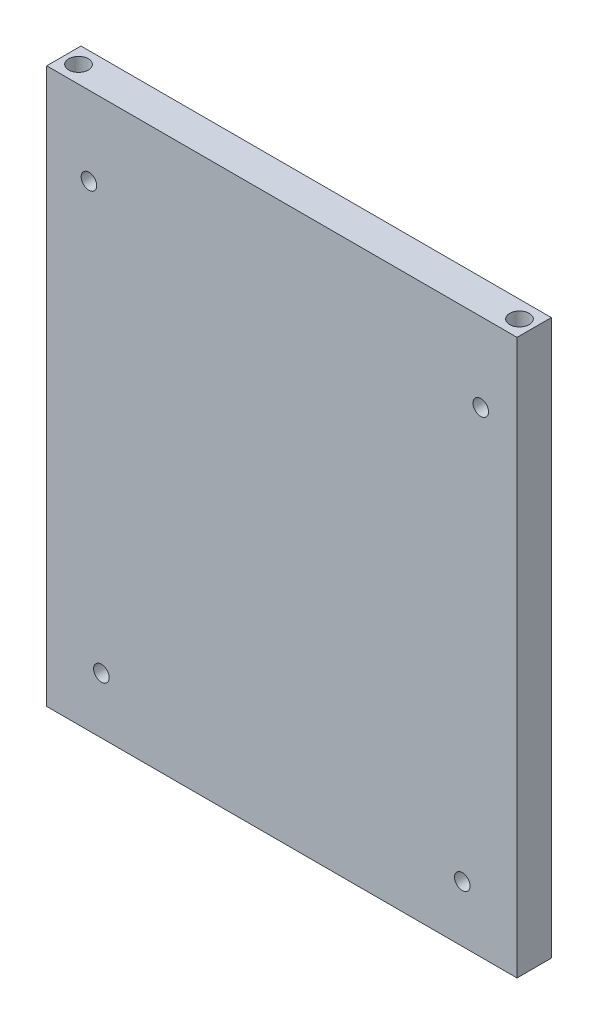
SolidWorks part; units mm, degrees
ref_plane "Front" through (0, 0, 0) normal (0, 0, 1) x (1, 0, 0)
ref_plane "Top" through (0, 0, 0) normal (0, 1, 0) x (1, 0, 0)
ref_plane "Right" through (0, 0, 0) normal (1, 0, 0) x (0, 0, -1)
sketch "Sketch1" plane through (0, 0, 0) normal (0, 0, 1) x (1, 0, 0)
  line L1 (-160.8649, 98.9879) -> (-64.8649, 98.9879)
  line L2 (-160.8649, 98.9879) -> (-160.8649, -14.2521)
  line L3 (-160.8649, -14.2521) -> (-64.8649, -14.2521)
  line L4 (-64.8649, 98.9879) -> (-64.8649, -14.2521)
  dimension "D1" = 96
  dimension "D2" = 113.24
extrude "Boss-Extrude1" add sketch "Sketch1" along normal blind 7
sketch "Sketch2" plane through (0, 0, 7) normal (0, 0, 1) x (1, 0, 0)
  line L0 (-160.8649, 98.9879) -> (-160.8649, -14.2521) construction
  circle A0 centre (-152.2349, 82.8995) radius 1.59
  circle A1 centre (-72.2649, 82.8995) radius 1.59
  circle A2 centre (-149.6949, -2.7929) radius 1.59
  circle A3 centre (-76.0349, -2.7929) radius 1.59
  point P8 (-74.7679, -2.2323)
  point P9 (-79.5481, 83.3247)
  point P10 (-142.9834, -2.2342)
  point P11 (-149.1848, 83.3247)
  point P12 (0, 0)
  point P13 (0, 0)
  point P14 (-82.132, -2.7929)
  point P15 (0, 0)
  point P16 (0, 0)
  dimension "D5" = 3.18
  dimension "D1" = 73.66
  dimension "D2" = 85.73
  dimension "D3" = 2.54
  dimension "D4" = 3.77
  dimension "D6" = 11.17
extrude "Cut-Extrude1" cut sketch "Sketch2" against normal blind 10
sketch "Sketch4" plane through (0, 98.9879, 0) normal (0, 1, 0) x (1, 0, 0)
  line L5 (-64.8649, -7) -> (-64.8649, 0) construction
  line L10 (-160.8649, -7) -> (-160.8649, 0) construction
  circle A0 centre (-67.8649, -3.5) radius 2
  circle A1 centre (-157.8649, -3.5) radius 2
  point P12 (-68.3649, 0)
  point P13 (-64.8649, -3.5)
  point P16 (-157.3649, 0)
  dimension "D3" = 4
  dimension "D1" = 3
  dimension "D2" = 3
extrude "Cut-Extrude3" cut sketch "Sketch4" against normal through all
